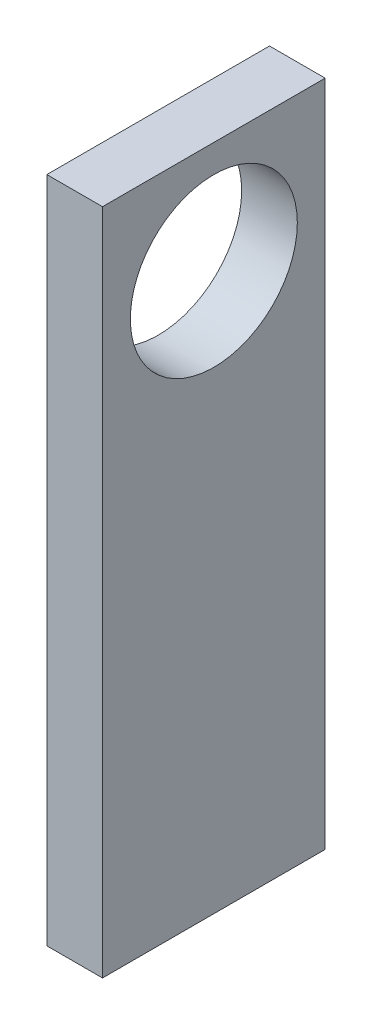
SolidWorks part; units mm, degrees
ref_plane "前视基准面" through (0, 0, 0) normal (0, 0, 1) x (1, 0, 0)
ref_plane "上视基准面" through (0, 0, 0) normal (0, 1, 0) x (1, 0, 0)
ref_plane "右视基准面" through (0, 0, 0) normal (1, 0, 0) x (0, 0, -1)
sketch "草图1" plane through (0, 0, 0) normal (1, 0, 0) x (0, 0, -1)
  line L0 (-10, -10) -> (-10, -50)
  line L1 (-10, -50) -> (10, -50)
  line L2 (10, -10) -> (10, 10)
  line L3 (10, 10) -> (-10, 10)
  line L4 (-10, -10) -> (-10, 10)
  line L5 (10, -10) -> (-10, 10) construction
  line L6 (10, 10) -> (-10, -10) construction
  line L7 (10, -50) -> (10, -10)
  circle A0 centre (0, 0) radius 7.5
  dimension "D1" = 20
  dimension "D4" = 15
  dimension "D2" = 20
  dimension "D3" = 40
extrude "凸台-拉伸1" add sketch "草图1" along normal blind 5
